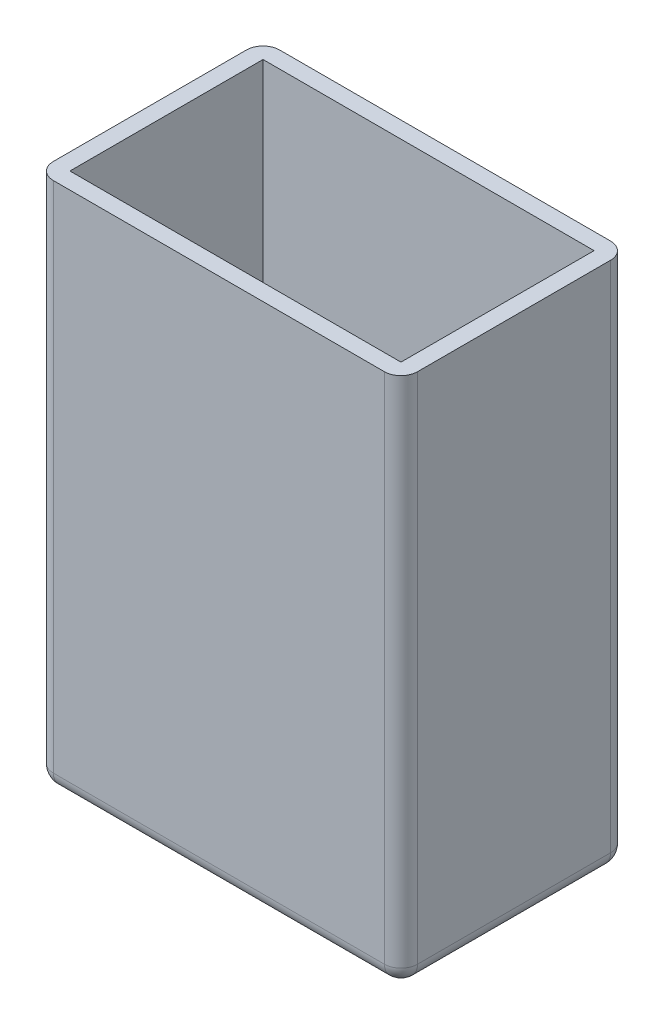
SolidWorks part; units mm, degrees
ref_plane "Ön Düzlem" through (0, 0, 0) normal (1, 0, 0) x (0, 1, 0)
ref_plane "Üst Düzlem" through (0, 0, 0) normal (0, 0, 1) x (0, 1, 0)
ref_plane "Sağ Düzlem" through (0, 0, 0) normal (0, 1, 0) x (-1, 0, 0)
sketch "Çizim1" plane through (0, 0, 0) normal (0, 0, 1) x (0, 1, 0)
  line L0 (0, 0) -> (90, 0)
  line L1 (0, 0) -> (0, -60)
  line L2 (0, -60) -> (90, -60)
  line L3 (90, -60) -> (90, 0)
extrude "Yükseklik-Ekstrüzyon1" add sketch "Çizim1" along normal blind 3
sketch "Çizim2" plane through (0, 0, 0) normal (0, 0, 1) x (0, 1, 0)
  line L0 (0, 0) -> (0, -60)
  line L1 (0, -60) -> (90, -60)
  line L3 (90, -60) -> (90, 0)
  line L5 (90, 0) -> (0, 0)
  line L8 (-3, 3) -> (93, 3)
  line L9 (93, 3) -> (93, -63)
  line L10 (93, -63) -> (-3, -63)
  line L11 (-3, -63) -> (-3, 3)
extrude "Yükseklik-Ekstrüzyon2" add sketch "Çizim2" along normal blind 38
sketch "Çizim3" plane through (0, 0, 38) normal (0, 0, 1) x (1, 0, 0)
  line L0 (0, 90) -> (0, 93)
  line L1 (63, 93) -> (-3, 93) construction
  line L2 (0, 90) -> (60, 90)
  line L3 (60, 90) -> (60, 93)
  line L4 (60, 93) -> (0, 93)
extrude "Kes-Ekstrüzyon1" cut sketch "Çizim3" against normal blind 35
sketch "Çizim4" plane through (0, 0, 38) normal (0, 0, 1) x (1, 0, 0)
  line L0 (-3, 93) -> (63, 93)
  line L1 (63, 93) -> (63, -3)
  line L2 (63, -3) -> (-3, -3)
  line L3 (-3, -3) -> (-3, 93)
extrude "Yükseklik-Ekstrüzyon3" add sketch "Çizim4" along normal blind 3
fillet "Radyus4" radius 3 1 edges at (-3, -3, 20.5)
fillet "Radyus5" radius 3 1 edges at (63, -3, 20.5)
fillet "Radyus6" radius 3 5 edges at (-3, 46.5, 41) (30, -3, 41) (-2.1213, -2.1213, 41) (63, 46.5, 41) (62.1213, -2.1213, 41)
fillet "Radyus7" radius 3 5 edges at (-3, 46.5, 0) (30, -3, 0) (-2.1213, -2.1213, 0) (63, 46.5, 0) (62.1213, -2.1213, 0)
